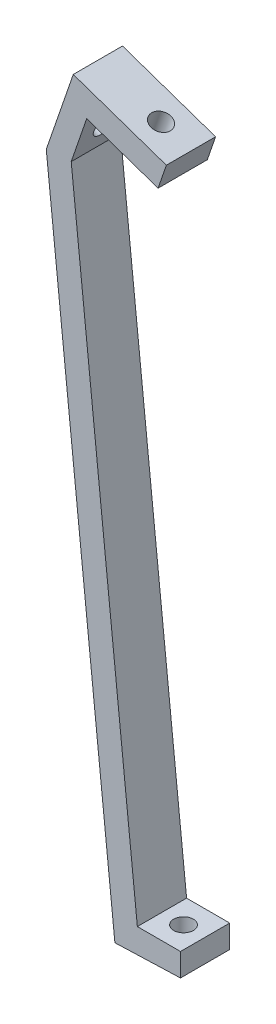
SolidWorks part; units mm, degrees
ref_plane "Alzado" through (0, 0, 0) normal (0, 0, 1) x (1, 0, 0)
ref_plane "Planta" through (0, 0, 0) normal (0, 1, 0) x (1, 0, 0)
ref_plane "Vista lateral" through (0, 0, 0) normal (1, 0, 0) x (0, 0, -1)
sketch "Croquis1" plane through (0, 0, 0) normal (0, 0, 1) x (1, 0, 0)
  line L2 (32.7916, 90.2645) -> (24.386, 93.1588)
  line L3 (-2.9617, 13.7352) -> (24.386, 93.1588)
  line L4 (24.386, 93.1588) -> (23.0837, 89.3767) construction
  line L5 (23.0837, 89.3767) -> (35.4622, 85.1144)
  line L6 (36.6017, 88.4238) -> (39.2492, 87.5122)
  line L7 (39.2492, 87.5122) -> (37.3609, 82.0282)
  line L8 (34.3227, 81.8051) -> (36.6017, 88.4238)
  line L9 (34.3227, 81.8051) -> (42.685, 2.2434)
  line L11 (37.3609, 82.0282) -> (45.423, 5.3226)
  line L12 (42.685, 2.2434) -> (50.6801, 2.5226)
  line L13 (50.6801, 2.5226) -> (50.6801, 5.3226)
  line L14 (50.6801, 5.3226) -> (45.423, 5.3226)
  point P11 (35.4622, 85.1144)
  dimension "D1" = 4
  dimension "D2" = 7
  dimension "D3" = 2.8
  dimension "D4" = 96
  dimension "D5" = 8
  dimension "D6" = 2.8
  dimension "D7" = 5.8
  dimension "D8" = 80
  dimension "D9" = 155
extrude "Saliente-Extruir1" add sketch "Croquis1" along normal mid plane 6 contours L11 L14 L13 L12 L9 L8 L6 L7
sketch "Croquis2" plane through (8.15, -2.8063, 0) normal (0.9455, -0.3256, 0) x (0, 0, -1)
  line L0 (-3, 95.5227) -> (3, 89.7227) construction
  circle A0 centre (0, 92.6227) radius 1.2
  dimension "D1" = 2.4
extrude "Cortar-Extruir1" cut sketch "Croquis2" against normal up to next
sketch "Croquis3" plane through (0, 5.3226, 0) normal (0, 1, 0) x (1, 0, 0)
  line L0 (45.423, -3) -> (50.6801, 3) construction
  circle A0 centre (48.0516, 0) radius 1.2
  dimension "D1" = 2.4
extrude "Cortar-Extruir2" cut sketch "Croquis3" against normal up to next
sketch "Croquis4" plane through (0, 0, 3) normal (0, 0, 1) x (1, 0, 0)
  line L0 (36.6017, 88.4238) -> (37.611, 91.3549)
  line L1 (34.3227, 81.8051) -> (36.6017, 88.4238) construction
  line L2 (37.611, 91.3549) -> (48.9572, 87.448)
  line L3 (48.9572, 87.448) -> (47.9479, 84.5169)
  line L4 (47.9479, 84.5169) -> (36.6017, 88.4238)
  dimension "D1" = 3.1
  dimension "D2" = 12
extrude "Saliente-Extruir2" add sketch "Croquis4" against normal up to vertex (6 mm away)
sketch "Croquis5" plane through (32.1084, 93.2496, 0) normal (0.3256, 0.9455, 0) x (0.9455, -0.3256, 0)
  line L0 (5.8196, 0) -> (13.9596, 0) construction
  line L1 (5.8196, 3) -> (5.8196, -3) construction
  circle A0 centre (13.9596, 0) radius 1.2
  dimension "D2" = 2.4
  dimension "D1" = 8.14
extrude "Cortar-Extruir3" cut sketch "Croquis5" against normal up to next contours A0
